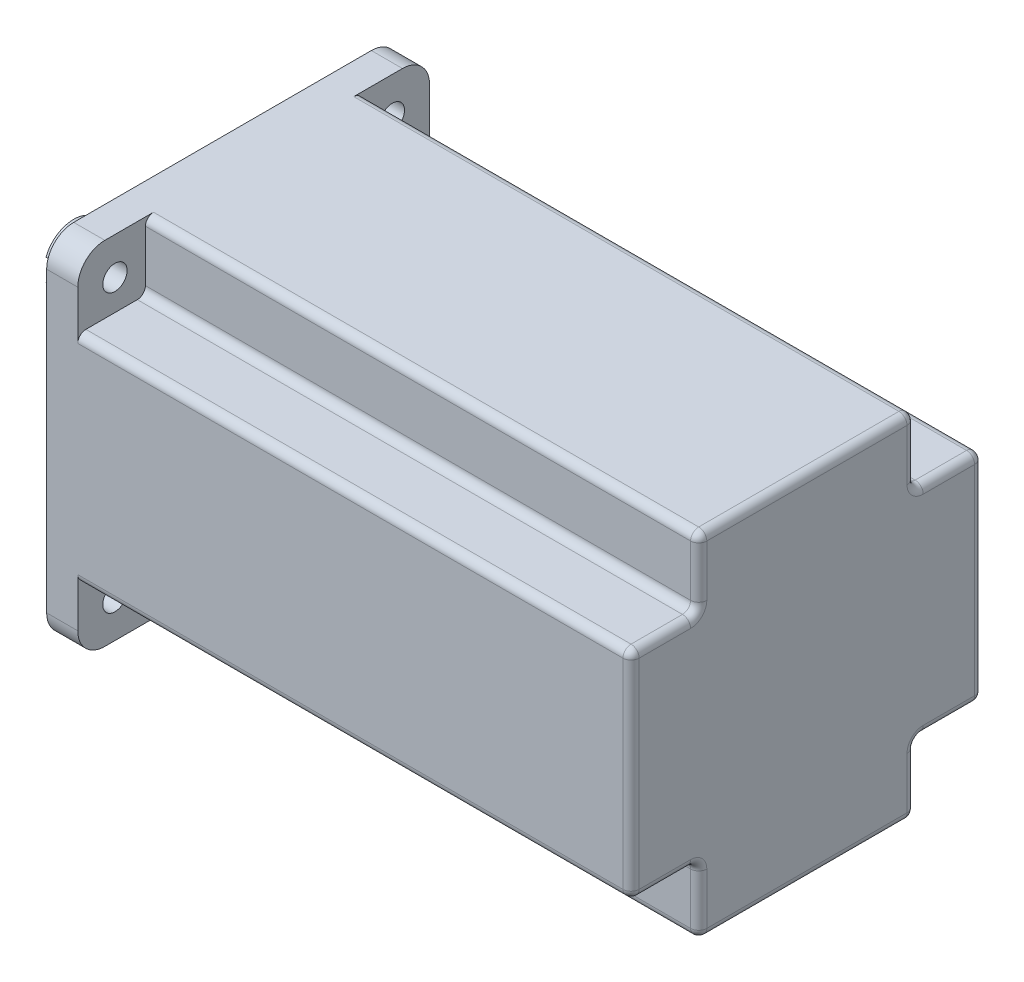
SolidWorks part; units mm, degrees
ref_plane "Front Plane" through (0, 0, 0) normal (0, 0, 1) x (1, 0, 0)
ref_plane "Top Plane" through (0, 0, 0) normal (0, 1, 0) x (1, 0, 0)
ref_plane "Right Plane" through (0, 0, 0) normal (1, 0, 0) x (0, 0, -1)
sketch "Sketch1" plane through (0, 0, 0) normal (1, 0, 0) x (0, 0, -1)
  line L1 (-65, -65) -> (65, -65)
  line L2 (-65, -65) -> (-65, 65)
  line L3 (-65, 65) -> (65, 65)
  line L4 (65, -65) -> (65, 65)
  line L5 (-65, -65) -> (65, 65) construction
  line L6 (-65, 65) -> (65, -65) construction
  point P0 (0, 0)
  dimension "D1" = 130
extrude "Boss-Extrude1" add sketch "Sketch1" along normal blind 11.5
fillet "Fillet1" radius 10 4 edges at (5.75, -65, 65) (5.75, -65, -65) (5.75, 65, -65) (5.75, 65, 65)
sketch "Sketch2" plane through (11.5, 0, 0) normal (1, 0, 0) x (0, 0, -1)
  line L0 (55, 65) -> (-55, 65) construction
  line L1 (-40, 65) -> (40, 65)
  line L2 (-40, 65) -> (-40, 40)
  line L3 (-40, -65) -> (40, -65)
  line L4 (40, 65) -> (40, 40)
  line L5 (-55, -65) -> (55, -65) construction
  line L6 (65, -55) -> (65, 55) construction
  line L7 (65, 40) -> (40, 40)
  line L8 (65, 40) -> (65, -40)
  line L9 (65, -40) -> (40, -40)
  line L10 (-65, 40) -> (-65, -40)
  line L11 (-65, 55) -> (-65, -55) construction
  line L12 (65, 0) -> (0, 0) construction
  line L13 (0, 0) -> (0, 65) construction
  line L14 (40, -40) -> (40, -65)
  line L15 (-40, 40) -> (-65, 40)
  line L16 (-40, -40) -> (-40, -65)
  line L17 (-40, -40) -> (-65, -40)
  dimension "D1" = 25
extrude "Boss-Extrude2" add sketch "Sketch2" along normal blind 204.5
sketch "Sketch3" plane through (0, 0, 0) normal (-1, 0, 0) x (0, 0, 1)
  circle A0 centre (0, 0) radius 55
  dimension "D1" = 110
extrude "Boss-Extrude3" add sketch "Sketch3" along normal blind 6
sketch "Sketch4" plane through (0, 0, 0) normal (-1, 0, 0) x (0, 0, 1)
  circle A0 centre (0, 0) radius 11
  dimension "D1" = 22
extrude "Boss-Extrude4" add sketch "Sketch4" along normal blind 55
sketch "Sketch6" plane through (0, 0, 0) normal (0, 0, 1) x (1, 0, 0)
  line L0 (-55, 0) -> (-23, 0) construction
  line L1 (-55, 11) -> (-55, -11) construction
  line L2 (-55, 4) -> (-23, 4)
  line L3 (-55, -4) -> (-23, -4)
  arc A0 (-55, 4) -> (-55, -4) centre (-55, 0) ccw
  arc A1 (-23, -4) -> (-23, 4) centre (-23, 0) ccw
  point P5 (-39, 0)
  dimension "D1" = 8
  dimension "D2" = 32
extrude "Cut-Extrude1" cut sketch "Sketch6" along normal blind 113 from offset 7
hole_wizard "M6x1.0 Tapped Hole1" positions "Sketch7" profile "Sketch8" tap size "M6x1.0" standard "ANSI Metric"
sketch "Sketch7" plane through (-55, 0, 0) normal (-1, 0, 0) x (0, 0, 1)
  point P0 (0, 0)
sketch "Sketch8" plane through (-55, 0, 0) normal (0, 1, 0) x (0, 0, 1)
  line L0 (0, 0) -> (0, 21.5022)
  line L1 (0, 21.5022) -> (2.5, 20)
  line L2 (2.5, 20) -> (2.5, 0.525)
  line L3 (2.5, 0.525) -> (3.025, 0)
  line L5 (3.025, 0) -> (0, 0)
  line L6 (-2.5, 0.525) -> (-3.025, 0) construction
  line L10 (0, 21.5022) -> (-2.5, 20) construction
  line L11 (0, -6.35) -> (0, 107.95) construction
  dimension "Tap Drill Dia." = 5
  dimension "Tap Drill Depth" = 20
  dimension "Near C'Sink Dia." = 6.05
  dimension "Near C'Sink Angle" = 90
  dimension "Drill Angle" = 118
cosmetic thread "Hole Thread1" parameters "D1"=20, "D2"=6
sketch "Sketch9" plane through (0, 0, 0) normal (-1, 0, 0) x (0, 0, 1)
  line L1 (-51.2652, -51.2652) -> (51.2652, -51.2652) construction
  line L2 (-51.2652, -51.2652) -> (-51.2652, 51.2652) construction
  line L3 (-51.2652, 51.2652) -> (51.2652, 51.2652) construction
  line L4 (51.2652, -51.2652) -> (51.2652, 51.2652) construction
  line L5 (-51.2652, -51.2652) -> (51.2652, 51.2652) construction
  line L6 (-51.2652, 51.2652) -> (51.2652, -51.2652) construction
  circle A0 centre (51.2652, 51.2652) radius 4.5
  circle A1 centre (51.2652, -51.2652) radius 4.5
  circle A2 centre (-51.2652, -51.2652) radius 4.5
  circle A3 centre (-51.2652, 51.2652) radius 4.5
  point P0 (0, 0)
  dimension "D2" = 9
  dimension "D1" = 145
extrude "Cut-Extrude2" cut sketch "Sketch9" against normal blind 20
fillet "Fillet2" radius 3 24 edges at (113.75, 65, 40) (113.75, 40, 40) (113.75, 40, 65) (113.75, -40, 65) (113.75, -40, 40) (113.75, -65, 40) (113.75, -65, -40) (113.75, -40, -40) (113.75, -40, -65) (113.75, 40, -65) (113.75, 40, -40) (113.75, 65, -40) (216, 65, 0) (216, 52.5, -40) (216, 40, -52.5) (216, 0, -65) (216, -40, -52.5) (216, -52.5, -40) (216, -65, 0) (216, -52.5, 40) (216, -40, 52.5) (216, 0, 65) (216, 40, 52.5) (216, 52.5, 40)
